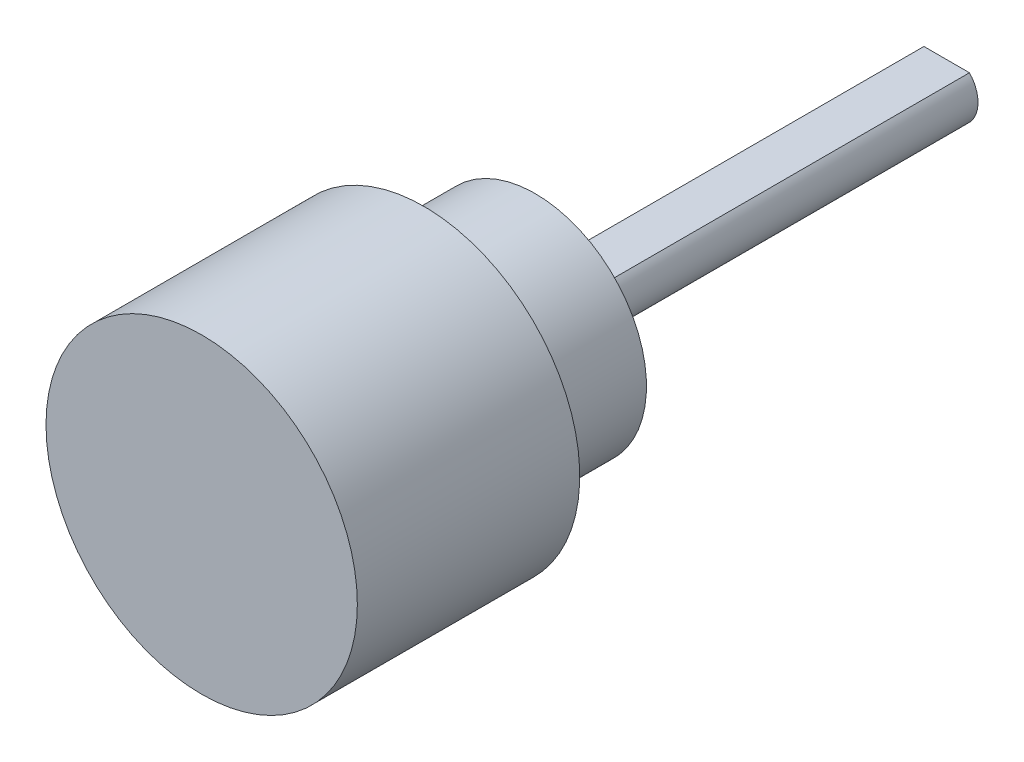
SolidWorks part; units mm, degrees
ref_plane "Plan de face" through (0, 0, 0) normal (0, 0, 1) x (1, 0, 0)
ref_plane "Plan de dessus" through (0, 0, 0) normal (0, 1, 0) x (1, 0, 0)
ref_plane "Plan de droite" through (0, 0, 0) normal (1, 0, 0) x (0, 0, -1)
sketch "Esquisse1" plane through (0, 0, 0) normal (0, 0, 1) x (1, 0, 0)
  circle A0 centre (0, 0) radius 14
extrude "Boss.-Extru.1" add sketch "Esquisse1" along normal blind 20
sketch "Esquisse2" plane through (0, 0, 0) normal (0, 0, -1) x (-1, 0, 0)
  line L0 (-2.0477, 1.9333) -> (2.0477, 1.9333)
  arc A1 (-2.0477, 1.9333) -> (2.0477, 1.9333) centre (0, 0) ccw
  point P4 (0, 0)
extrude "Boss.-Extru.2" add sketch "Esquisse2" along normal blind 47
sketch "Esquisse3" plane through (0, 0, 0) normal (0, 0, -1) x (-1, 0, 0)
  circle A0 centre (0, 0) radius 18
extrude "Boss.-Extru.3" add sketch "Esquisse3" along normal blind 2
sketch "Esquisse4" plane through (0, 0, -2) normal (0, 0, -1) x (-1, 0, 0)
  circle A0 centre (0, 0) radius 10
extrude "Boss.-Extru.4" add sketch "Esquisse4" along normal blind 8
sketch "Esquisse5" plane through (0, 0, -2) normal (0, 0, -1) x (-1, 0, 0)
  line L1 (0, 18) -> (50, 18)
  line L2 (60, 8) -> (60, -8)
  line L3 (50, -18) -> (0, -18)
  circle A0 centre (0, 0) radius 18 construction
  arc A1 (60, -8) -> (50, -18) centre (50, -8) cw
  arc A2 (60, 8) -> (50, 18) centre (50, 8) ccw
  arc A3 (0, 18) -> (0, -18) centre (0, 0) cw
  circle M5 centre (0, 0) radius 18
  dimension "D1" = 10
extrude "Boss.-Extru.5" add sketch "Esquisse5" against normal blind 2 contours L2 A2 L1 L3 A1 M5
sketch "Esquisse6" plane through (0, 0, -2) normal (0, 0, -1) x (-1, 0, 0)
  line L0 (0, 18) -> (-22.5046, 18)
  line L1 (-22.5046, 18) -> (-22.5046, -18)
  line L2 (-22.5046, -18) -> (62.102, -18)
  line L3 (62.102, -18) -> (62.102, 18)
  line L4 (62.102, 18) -> (0, 18)
  circle A0 centre (0, 0) radius 10
  arc A1 (0, 18) -> (0, -18) centre (0, 0) ccw construction
extrude "Enlèv. mat.-Extru.1" cut sketch "Esquisse6" against normal blind 2
